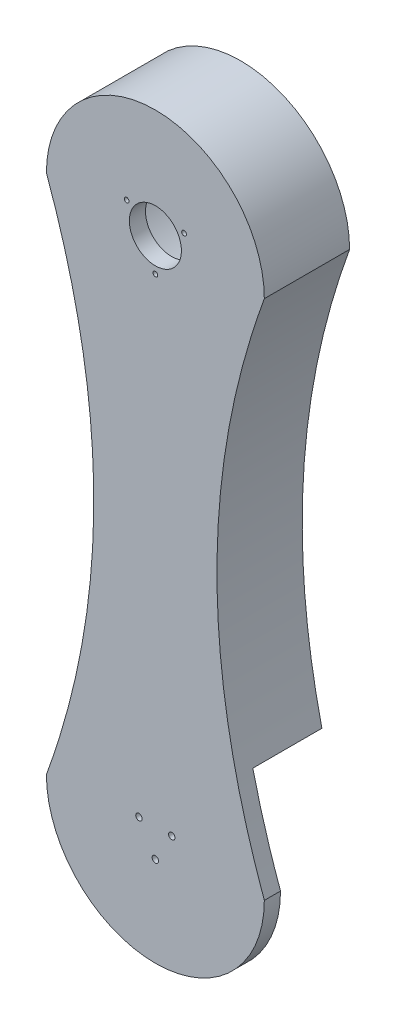
SolidWorks part; units mm, degrees
ref_plane "Front Plane" through (0, 0, 0) normal (1, 0, 0) x (0, 1, 0)
ref_plane "Top Plane" through (0, 0, 0) normal (0, 0, 1) x (0, 1, 0)
ref_plane "Right Plane" through (0, 0, 0) normal (0, 1, 0) x (-1, 0, 0)
sketch "Sketch1" plane through (0, 0, 0) normal (0, 0, 1) x (0, 1, 0)
  line L0 (0, 0) -> (550, 0) construction
  arc A0 (0, 115) -> (0, -115) centre (0, 0) ccw
  arc A1 (550, -115) -> (550, 115) centre (550, 0) ccw
  spline S0 degree 2 poles (0, 115) (275, 15) (550, 115) knots 0 0 0 1 1 1
  spline S1 degree 2 poles (0, -115) (275, -15) (550, -115) knots 0 0 0 1 1 1
  point P12 (275, 0)
  dimension "D1" = 230
  dimension "D2" = 550
  dimension "D3" = 130
extrude "Boss-Extrude1" add sketch "Sketch1" along normal blind 90
sketch "Sketch2" plane through (0, 0, 0) normal (0, 0, -1) x (1, 0, 0)
  circle A0 centre (0, 0) radius 97.5
  dimension "D1" = 195
extrude "Cut-Extrude1" cut sketch "Sketch2" against normal blind 72.91
sketch "Sketch6" plane through (0, 0, 0) normal (0, 0, -1) x (1, 0, 0)
  circle A0 centre (0, -550) radius 97.5
  circle A1 centre (0, 0) radius 97.5 construction
extrude "Cut-Extrude5" cut sketch "Sketch6" against normal blind 72.91
sketch "Sketch7" plane through (0, 0, 72.91) normal (0, 0, -1) x (1, 0, 0)
  circle A0 centre (0, -550) radius 27.5
  dimension "D1" = 55
extrude "Cut-Extrude6" cut sketch "Sketch7" against normal blind 72.91
sketch "Sketch10" plane through (0, 0, 0) normal (0, 0, -1) x (1, 0, 0)
  arc A1 (115, 0) -> (-115, 0) centre (0, 0) ccw construction
  arc A2 (115, 0) -> (-115, 0) centre (0, 0) ccw
  arc A3 (-85.7856, -97.6916) -> (85.7856, -97.6916) centre (0, 76.8839) ccw
  parabola Q0 (-115, -550) -> (-115, 0) focus (-443.125, -275) apex (-65, -275) construction
  parabola Q1 (-85.7856, -97.6916) -> (-115, 0) focus (-443.125, -275) apex (-65, -275)
  parabola Q2 (115, 0) -> (115, -550) focus (443.125, -275) apex (65, -275) construction
  parabola Q3 (115, 0) -> (85.7856, -97.6916) focus (443.125, -275) apex (65, -275)
  parabola Q4 (-115, -550) -> (-115, 0) focus (-443.125, -275) apex (-65, -275) construction
extrude "Cut-Extrude10" cut sketch "Sketch10" against normal up to surface (72.91 mm away) up to face at (-97.5, 0, 72.91)
sketch "Sketch13" plane through (0, 0, 72.91) normal (0, 0, -1) x (1, 0, 0)
  line L0 (0, 0) -> (0, 20) construction
  line L1 (0, 0) -> (-17.3205, -10) construction
  line L2 (0, 0) -> (17.3205, -10) construction
  circle A3 centre (0, 20) radius 3.4
  circle A4 centre (-17.3205, -10) radius 3.4
  circle A5 centre (17.3205, -10) radius 3.4
  dimension "D2" = 20
  dimension "D4" = 120
  dimension "D1" = 6.8
  dimension "D3" = 120
extrude "Cut-Extrude13" cut sketch "Sketch13" against normal up to surface (17.09 mm away) up to face at (-27.5, 550, 90)
sketch "Sketch14" plane through (0, 0, 90) normal (0, 0, 1) x (1, 0, 0)
  line L0 (0, 550) -> (0, 515) construction
  circle A0 centre (0, 515) radius 2.5
  dimension "D1" = 5
  dimension "D2" = 35
extrude "Cut-Extrude14" cut sketch "Sketch14" against normal up to surface (17.09 mm away) up to face at (-27.5, 550, 72.91)
pattern_circular "CirPattern1" count 3 every 120 about axis through (0, 550, 0) along (0, 0, 1) of "Cut-Extrude14"
